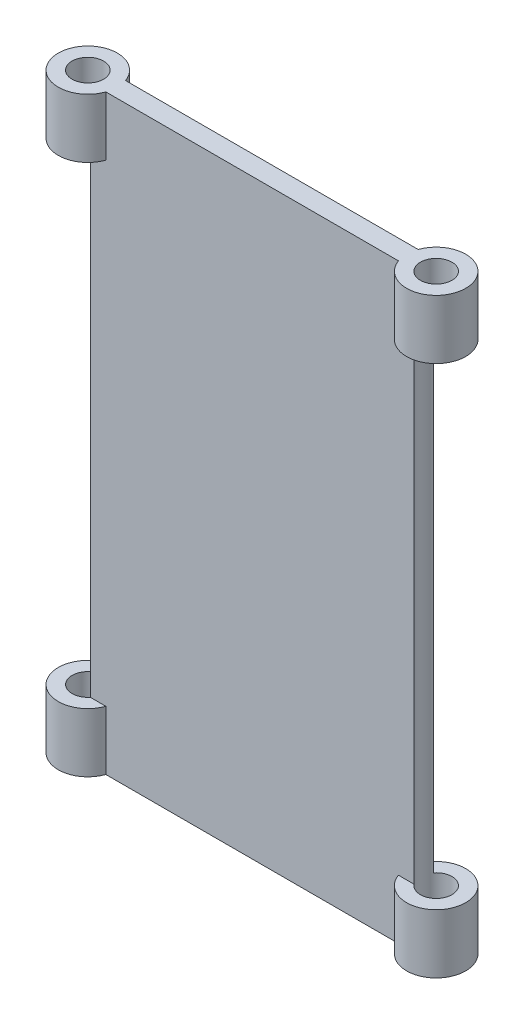
SolidWorks part; units mm, degrees
ref_plane "정면" through (0, 0, 0) normal (0, 0, 1) x (1, 0, 0)
ref_plane "윗면" through (0, 0, 0) normal (0, 1, 0) x (1, 0, 0)
ref_plane "우측면" through (0, 0, 0) normal (1, 0, 0) x (0, 0, -1)
sketch "스케치1" plane through (0, 0, 0) normal (0, 0, 1) x (1, 0, 0)
  line L1 (0, 0) -> (88.39, 0)
  line L2 (0, 0) -> (0, 150)
  line L3 (0, 150) -> (88.39, 150)
  line L4 (88.39, 0) -> (88.39, 150)
  dimension "D1" = 88.39
  dimension "D2" = 150
extrude "보스-돌출1" add sketch "스케치1" along normal blind 5
sketch "스케치2" plane through (0, 150, 0) normal (0, 1, 0) x (1, 0, 0)
  line L0 (88.39, -5) -> (88.39, 0) construction
  line L1 (0, -5) -> (0, 0) construction
  circle A0 centre (88.39, -2.5) radius 7.5
  circle A1 centre (0, -2.5) radius 7.5
  dimension "D1" = 15
  dimension "D2" = 15
extrude "보스-돌출2" add sketch "스케치2" against normal blind 15
hole_wizard "구멍1" positions "스케치3" profile "스케치4" legacy end condition through all
sketch "스케치3" plane through (0, 150, 0) normal (0, 1, 0) x (1, 0, 0)
  point P0 (0, -2.5)
  point P3 (88.39, -2.5)
sketch "스케치4" plane through (0, 150, 2.5) normal (1, 0, 0) x (0, 0, 1)
  line L0 (0, 0) -> (0, 150)
  line L1 (0, 150) -> (4, 150)
  line L2 (4, 150) -> (4, 0)
  line L3 (4, 0) -> (0, 0)
  line L4 (0, 110) -> (0, -10) construction
  dimension "지름" = 8
  dimension "깊이" = 150
sketch "스케치6" plane through (0, 0, 0) normal (0, 0, -1) x (-1, 0, 0)
  line L0 (-44.195, 150) -> (-44.195, -8.7542) construction
  line L1 (-81.3189, 150) -> (-7.0711, 150) construction
sketch "스케치7" plane through (0, 0, 0) normal (0, -1, 0) x (1, 0, 0)
  line L0 (81.3189, 0) -> (85.2675, 0)
  line L1 (81.3189, 5) -> (85.2675, 5)
  line L2 (85.2675, 5) -> (3.1225, 5)
  line L3 (3.1225, 0) -> (85.2675, 0)
  line L6 (3.1225, 5) -> (7.0711, 5)
  line L7 (3.1225, 0) -> (7.0711, 0)
  arc A2 (3.1225, 0) -> (3.1225, 5) centre (0, 2.5) ccw
  arc A3 (85.2675, 5) -> (85.2675, 0) centre (88.39, 2.5) ccw
  arc A4 (3.1225, 0) -> (3.1225, 5) centre (0, 2.5) ccw
  arc A5 (85.2675, 5) -> (85.2675, 0) centre (88.39, 2.5) ccw
  arc A6 (7.0711, 5) -> (7.0711, 0) centre (0, 2.5) ccw construction
  arc A8 (7.0711, 5) -> (7.0711, 0) centre (0, 2.5) ccw
  arc A10 (81.3189, 0) -> (81.3189, 5) centre (88.39, 2.5) ccw construction
  arc A12 (81.3189, 0) -> (81.3189, 5) centre (88.39, 2.5) ccw
  dimension "D1" = 0
extrude "보스-돌출3" add sketch "스케치7" against normal blind 15
sketch "스케치8" plane through (0, 15, 0) normal (0, 1, 0) x (1, 0, 0)
  circle A0 centre (0, -2.5) radius 4 construction
  circle A1 centre (88.39, -2.5) radius 4 construction
  circle A2 centre (0, -2.5) radius 4
  circle A3 centre (88.39, -2.5) radius 4
extrude "컷-돌출1" cut sketch "스케치8" against normal through all
